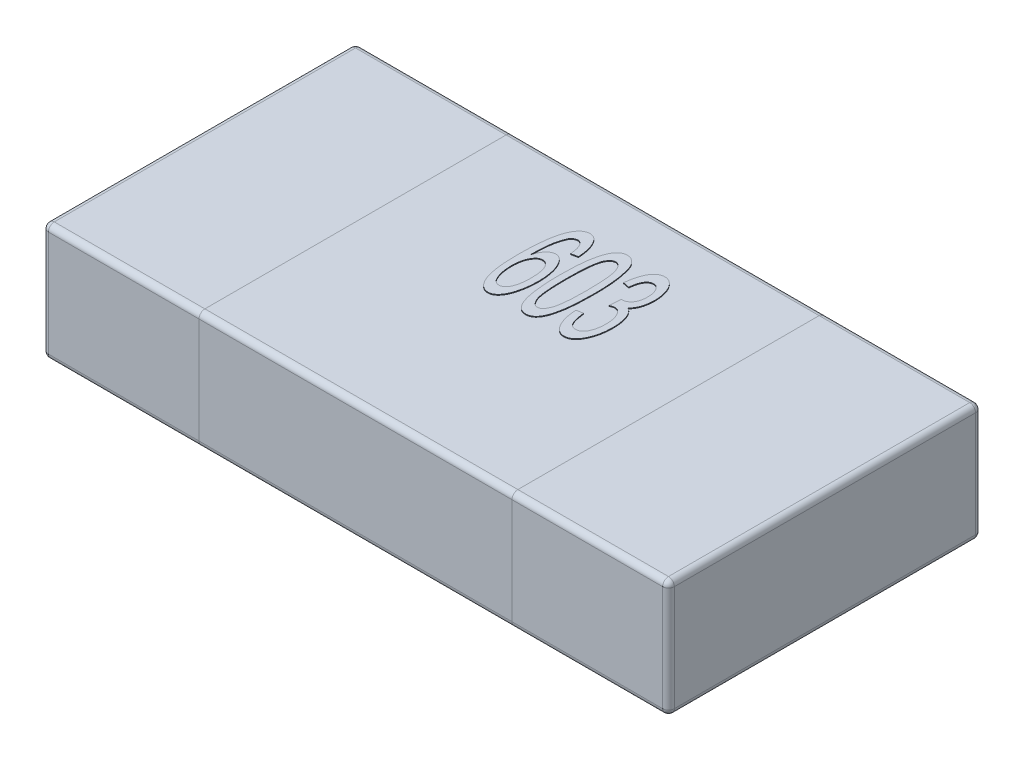
SolidWorks part; units mm, degrees
ref_plane "Front" through (0, 0, 0) normal (0, 0, 1) x (1, 0, 0)
ref_plane "Top" through (0, 0, 0) normal (0, 1, 0) x (1, 0, 0)
ref_plane "Right" through (0, 0, 0) normal (1, 0, 0) x (0, 0, -1)
sketch "Sketch1" plane through (0, 0, 0) normal (0, 1, 0) x (1, 0, 0)
  line L0 (0, -0.8174) -> (0, 0.9971) construction
  line L1 (-1.7635, 0) -> (2.4572, 0) construction
  line L3 (-0.8, 0.4) -> (0.8, 0.4)
  line L4 (-0.8, 0.4) -> (-0.8, -0.4)
  line L5 (-0.8, -0.4) -> (0.8, -0.4)
  line L6 (0.8, 0.4) -> (0.8, -0.4)
  dimension "D1" = 1.6
  dimension "D2" = 0.8
extrude "Extrude1" add sketch "Sketch1" along normal blind 0.3
fillet "Fillet1" radius 0.015 12 edges at (0, 0.3, 0.4) (-0.8, 0.15, -0.4) (0, 0, -0.4) (-0.8, 0, 0) (-0.8, 0.15, 0.4) (0, 0, 0.4) (0.8, 0.15, 0.4) (0.8, 0.15, -0.4) (0.8, 0, 0) (0, 0.3, -0.4) (0.8, 0.3, 0) (-0.8, 0.3, 0)
sketch "Sketch2" plane through (0, 0, 0.4) normal (0, 0, 1) x (1, 0, 0)
  line L0 (-0.785, 0.3) -> (0.785, 0.3) construction
  line L1 (-0.4, 0.3) -> (0.4, 0.3)
  line L2 (-0.4, 0.3) -> (-0.4, 0)
  line L3 (-0.4, 0) -> (0.4, 0)
  line L4 (0.4, 0.3) -> (0.4, 0)
  line L5 (0.785, 0) -> (-0.785, 0) construction
  line L7 (0, -0.2963) -> (0, 3.0124) construction
  line L8 (-0.8, 0.015) -> (-0.8, 0.285) construction
  dimension "D1" = 0.4
split line "Split Line1"
sketch "Sketch3" plane through (0, 0.3, 0) normal (0, 1, 0) x (1, 0, 0)
  text T0 "603" font "Arial" height in points 1
  dimension "D1" = 0.125
  dimension "D2" = 0.015
extrude "Extrude2" add sketch "Sketch3" along normal blind 0.002
